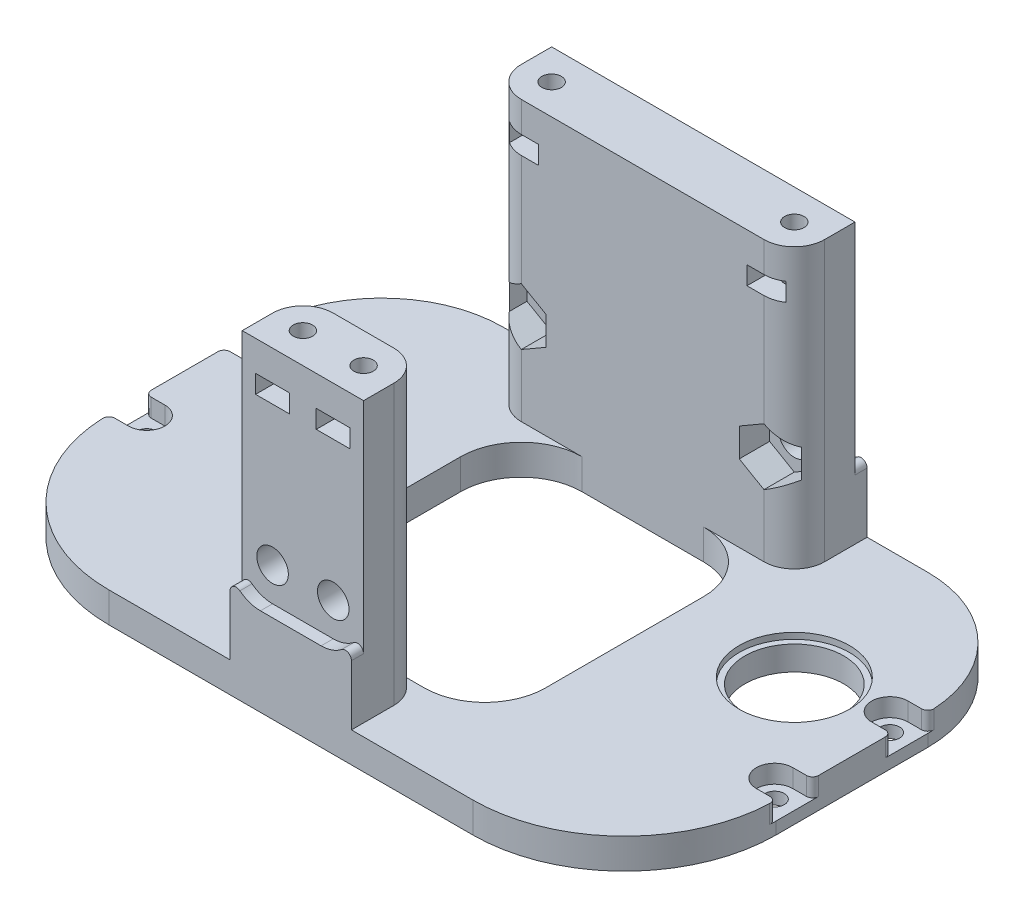
SolidWorks part; units mm, degrees
ref_plane "Alzado" through (0, 0, 0) normal (0, 0, 1) x (1, 0, 0)
ref_plane "Planta" through (0, 0, 0) normal (0, 1, 0) x (1, 0, 0)
ref_plane "Vista lateral" through (0, 0, 0) normal (1, 0, 0) x (0, 0, -1)
sketch "Croquis1" plane through (0, 0, 0) normal (0, 1, 0) x (1, 0, 0)
  line L5 (-30, -35) -> (30, -35)
  line L10 (-55, -10) -> (-55, 15)
  line L11 (-35, 35) -> (35, 35)
  line L12 (55, -10) -> (55, 15)
  line L13 (-55, -35) -> (55, 35) construction
  line L14 (-55, 35) -> (55, -35) construction
  line L15 (-10, -23) -> (10, -23)
  line L16 (-20, -13) -> (-20, 13)
  line L17 (-10, 23) -> (10, 23)
  line L18 (20, -13) -> (20, 13)
  line L19 (-20, -23) -> (20, 23) construction
  line L20 (-20, 23) -> (20, -23) construction
  line L21 (0, -55) -> (0, 55) construction
  line L22 (55, 2.5) -> (66.7183, 2.5) construction
  arc A14 (35, 35) -> (55, 15) centre (35, 15) cw
  arc A15 (-35, 35) -> (-55, 15) centre (-35, 15) ccw
  arc A16 (30, -35) -> (55, -10) centre (30, -10) ccw
  arc A17 (-30, -35) -> (-55, -10) centre (-30, -10) cw
  arc A18 (-10, -23) -> (-20, -13) centre (-10, -13) cw
  arc A19 (10, -23) -> (20, -13) centre (10, -13) ccw
  arc A20 (10, 23) -> (20, 13) centre (10, 13) cw
  arc A21 (-20, 13) -> (-10, 23) centre (-10, 13) cw
  circle A22 centre (39, 9) radius 8.15
  circle A23 centre (51.75, 12) radius 1.6
  circle A27 centre (-39, 9) radius 8.15
  circle A28 centre (51.75, -7) radius 1.6
  circle A29 centre (-51.75, -7) radius 1.6
  circle A30 centre (-51.75, 12) radius 1.6
  point P0 (0, 0)
  point P17 (0, 0)
  point P38 (55, 2.5)
  point P39 (66.7183, 2.5)
  dimension "D3" = 20
  dimension "D4" = 25
  dimension "D7" = 10
  dimension "D8" = 3.2
  dimension "D9" = 16.3
  dimension "D1" = 110
  dimension "D2" = 70
  dimension "D5" = 46
  dimension "D6" = 40
  dimension "D10" = 9.5
  dimension "D11" = 3.25
  dimension "D12" = 16
  dimension "D13" = 6.5
extrude "Saliente-Extruir1" add sketch "Croquis1" along normal blind 5
sketch "Croquis2" plane through (0, 5, 0) normal (0, 1, 0) x (1, 0, 0)
  line L0 (0, -2.75) -> (0, 2.75) construction
  circle A0 centre (39, 9) radius 9.1
  circle A1 centre (-39, 9) radius 9.1
  dimension "D1" = 18.2
extrude "Cortar-Extruir1" cut sketch "Croquis2" against normal blind 1
sketch "Croquis3" plane through (0, 5, 0) normal (0, 1, 0) x (1, 0, 0)
  line L0 (51.75, 15) -> (55, 15)
  line L1 (51.75, 9) -> (55, 9)
  line L2 (55, -10) -> (55, 15) construction
  line L3 (55, 15) -> (55, 9)
  line L15 (55, 2.5) -> (62.9317, 2.5) construction
  line L16 (55, -10) -> (55, 15) construction
  line L17 (51.75, -10) -> (55, -10)
  line L18 (51.75, -4) -> (55, -4)
  line L19 (55, -10) -> (55, -4)
  line L20 (0, -2.75) -> (0, 2.75) construction
  line L21 (-51.75, -4) -> (-55, -4)
  line L22 (-55, -10) -> (-55, -4)
  line L23 (-51.75, -10) -> (-55, -10)
  line L24 (-51.75, 15) -> (-55, 15)
  line L25 (-51.75, 9) -> (-55, 9)
  line L26 (-55, 15) -> (-55, 9)
  arc A0 (51.75, 15) -> (51.75, 9) centre (51.75, 12) ccw
  arc A4 (51.75, -10) -> (51.75, -4) centre (51.75, -7) cw
  arc A5 (-51.75, -10) -> (-51.75, -4) centre (-51.75, -7) ccw
  arc A6 (-51.75, 15) -> (-51.75, 9) centre (-51.75, 12) cw
  dimension "D1" = 6
extrude "Cortar-Extruir2" cut sketch "Croquis3" against normal blind 3
fillet "Redondeo1" radius 1 8 edges at (55, 3.5, -9) (55, 3.5, -15) (-55, 3.5, -9) (-55, 3.5, -15) (-55, 3.5, 4) (-55, 3.5, 10) (55, 3.5, 10) (55, 3.5, 4)
sketch "Croquis4" plane through (0, 5, 0) normal (0, 1, 0) x (1, 0, 0)
  line L0 (35, 35) -> (-35, 35) construction
  line L1 (-25, 35) -> (25, 35)
  line L2 (-25, 35) -> (-25, 28)
  line L3 (-20, 23) -> (20, 23)
  line L4 (25, 35) -> (25, 28)
  line L5 (10, 23) -> (-10, 23) construction
  line L6 (0, -2.75) -> (0, 2.75) construction
  arc A0 (-25, 28) -> (-20, 23) centre (-20, 28) ccw
  arc A1 (20, 23) -> (25, 28) centre (20, 28) ccw
  point P9 (0, 23)
  dimension "D2" = 5
  dimension "D3" = 5
  dimension "D1" = 50
extrude "Saliente-Extruir2" add sketch "Croquis4" along normal blind 46
sketch "Croquis5" plane through (0, 0, -35) normal (0, 0, -1) x (-1, 0, 0)
  line L1 (-25, 51) -> (25, 51)
  line L3 (-20, 14.5) -> (20, 14.5)
  line L4 (25, 51) -> (25, 17.7087)
  line L5 (-25, 51) -> (-25, 17.7087)
  line L6 (-25, 51) -> (-25, 5) construction
  line L7 (0, 2.75) -> (0, -2.75) construction
  arc A0 (-25, 17.7087) -> (-20, 14.5) centre (-20, 20) ccw
  arc A1 (25, 17.7087) -> (20, 14.5) centre (20, 20) cw
  dimension "D2" = 11
  dimension "D1" = 36.5
  dimension "D3" = 5
extrude "Cortar-Extruir3" cut sketch "Croquis5" against normal blind 2
sketch "Croquis6" plane through (0, 0, -33) normal (0, 0, -1) x (-1, 0, 0)
  line L0 (-25, 51) -> (-25, 17.7087) construction
  line L1 (-22.8, 46) -> (-17.2, 46)
  line L2 (-22.8, 46) -> (-22.8, 43)
  line L3 (-22.8, 43) -> (-17.2, 43)
  line L4 (-17.2, 46) -> (-17.2, 43)
  line L5 (0, 2.75) -> (0, -2.75) construction
  line L6 (22.8, 43) -> (17.2, 43)
  line L7 (17.2, 46) -> (17.2, 43)
  line L8 (22.8, 46) -> (17.2, 46)
  line L9 (22.8, 46) -> (22.8, 43)
  circle A0 centre (-20, 20) radius 2.6
  circle A1 centre (20, 20) radius 2.6
  dimension "D1" = 5.2
  dimension "D2" = 5.6
  dimension "D3" = 3
  dimension "D4" = 5
  dimension "D5" = 2.2
extrude "Cortar-Extruir4" cut sketch "Croquis6" against normal up to surface (10 mm away) up to face at (0, 15.25, -23)
sketch "Croquis7" plane through (0, 0, -23) normal (0, 0, 1) x (1, 0, 0)
  line L1 (-20, 24.7) -> (-24.0703, 22.35)
  line L2 (-24.0703, 22.35) -> (-24.0703, 17.65)
  line L3 (-24.0703, 17.65) -> (-20, 15.3)
  line L4 (-20, 15.3) -> (-15.9297, 17.65)
  line L5 (-15.9297, 17.65) -> (-15.9297, 22.35)
  line L6 (-15.9297, 22.35) -> (-20, 24.7)
  line L7 (-20, 43) -> (-20, 22.6) construction
  line L8 (0, -2.75) -> (0, 2.75) construction
  line L9 (15.9297, 22.35) -> (20, 24.7)
  line L10 (15.9297, 17.65) -> (15.9297, 22.35)
  line L11 (20, 15.3) -> (15.9297, 17.65)
  line L12 (24.0703, 17.65) -> (20, 15.3)
  line L13 (24.0703, 22.35) -> (24.0703, 17.65)
  line L14 (20, 24.7) -> (24.0703, 22.35)
  circle A0 centre (-20, 20) radius 4.0703 construction
  dimension "D1" = 4.7
extrude "Cortar-Extruir5" cut sketch "Croquis7" against normal blind 5
sketch "Croquis8" plane through (0, 5, 0) normal (0, 1, 0) x (1, 0, 0)
  line L0 (0, -2.75) -> (0, 2.75) construction
  line L1 (-10, -35) -> (10, -35)
  line L2 (-10, -35) -> (-10, -28)
  line L3 (-5, -23) -> (5, -23)
  line L4 (10, -35) -> (10, -28)
  line L8 (-30, -35) -> (30, -35) construction
  line L9 (-10, -23) -> (10, -23) construction
  arc A0 (-10, -28) -> (-5, -23) centre (-5, -28) cw
  arc A1 (5, -23) -> (10, -28) centre (5, -28) cw
  point P18 (0, -35)
  dimension "D2" = 5
  dimension "D3" = 5
  dimension "D1" = 20
extrude "Saliente-Extruir3" add sketch "Croquis8" along normal blind 46
sketch "Croquis9" plane through (0, 0, 35) normal (0, 0, 1) x (1, 0, 0)
  line L0 (10, 51) -> (10, 17.7087)
  line L1 (-10, 51) -> (10, 51)
  line L3 (-5, 14.5) -> (5, 14.5)
  line L5 (-10, 51) -> (-10, 17.7087)
  line L6 (-10, 51) -> (-10, 5) construction
  line L7 (0, -2.75) -> (0, 2.75) construction
  arc A0 (-10, 17.7087) -> (-5, 14.5) centre (-5, 20) ccw
  arc A1 (10, 17.7087) -> (5, 14.5) centre (5, 20) cw
  line M12 (10, 5) -> (10, 51)
  line M13 (10, 51) -> (-10, 51)
  line M14 (-10, 51) -> (-10, 5)
  dimension "D2" = 11
  dimension "D1" = 36.5
  dimension "D3" = 5
  dimension "D4" = 5.5
extrude "Cortar-Extruir6" cut sketch "Croquis9" against normal blind 2 contours A1 A0 L3 M12 M13 M14
sketch "Croquis10" plane through (0, 0, 33) normal (0, 0, 1) x (1, 0, 0)
  line L0 (10, 51) -> (-10, 51) construction
  line L1 (-7.8, 46) -> (-2.2, 46)
  line L2 (-7.8, 46) -> (-7.8, 43)
  line L3 (-7.8, 43) -> (-2.2, 43)
  line L4 (-2.2, 46) -> (-2.2, 43)
  line L5 (-10, 51) -> (-10, 17.7087) construction
  line L6 (0, -2.75) -> (0, 2.75) construction
  line L7 (7.8, 43) -> (2.2, 43)
  line L8 (2.2, 46) -> (2.2, 43)
  line L9 (7.8, 46) -> (2.2, 46)
  line L10 (7.8, 46) -> (7.8, 43)
  circle A0 centre (-5, 20) radius 2.6
  circle A1 centre (5, 20) radius 2.6
  dimension "D1" = 5.2
  dimension "D2" = 3
  dimension "D3" = 5.6
  dimension "D4" = 5
  dimension "D5" = 2.2
extrude "Cortar-Extruir7" cut sketch "Croquis10" against normal up to surface (10 mm away) up to face at (0, 15.25, 23)
sketch "Croquis11" plane through (0, 51, 0) normal (0, 1, 0) x (1, 0, 0)
  line L0 (10, -33) -> (-10, -33) construction
  line L1 (-10, -28) -> (-10, -33) construction
  line L2 (-25, 33) -> (-25, 28) construction
  line L3 (-25, 33) -> (25, 33) construction
  line L4 (0, -2.75) -> (0, 2.75) construction
  circle A0 centre (-5, -28) radius 1.6
  circle A1 centre (-20, 28) radius 1.6
  circle A2 centre (5, -28) radius 1.6
  circle A3 centre (20, 28) radius 1.6
  dimension "D1" = 3.2
  dimension "D4" = 3.2
  dimension "D2" = 5
  dimension "D3" = 5
  dimension "D5" = 5
  dimension "D6" = 5
extrude "Cortar-Extruir8" cut sketch "Croquis11" against normal blind 21
fillet "Redondeo2" radius 1 4 edges at (-25, 17.7087, -34) (25, 17.7087, -34) (10, 17.7087, 34) (-10, 17.7087, 34)
